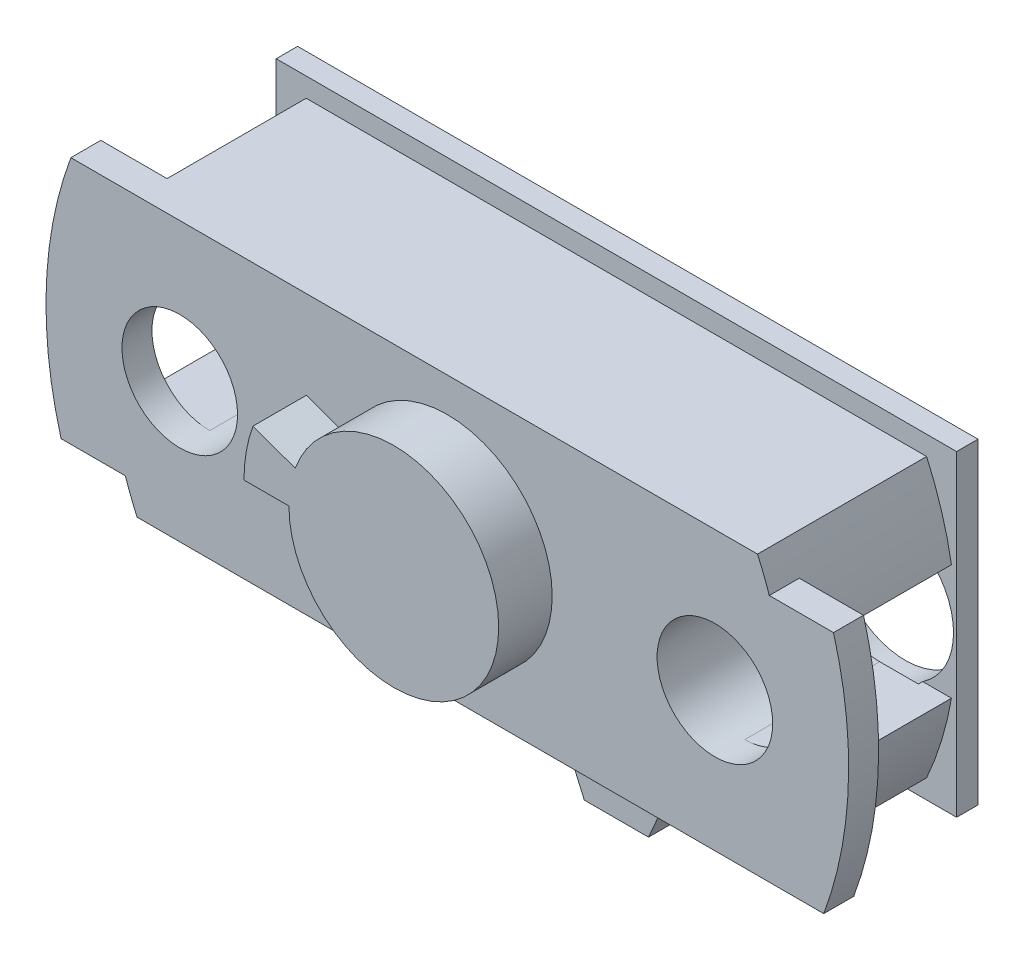
SolidWorks part; units mm, degrees
ref_plane "Přední rovina" through (0, 0, 0) normal (0, 0, 1) x (1, 0, 0)
ref_plane "Horní rovina" through (0, 0, 0) normal (0, 1, 0) x (1, 0, 0)
ref_plane "Pravá rovina" through (0, 0, 0) normal (1, 0, 0) x (0, 0, -1)
sketch "Skica1" plane through (0, 0, 0) normal (0, 0, 1) x (1, 0, 0)
  line L0 (-17.5873, 6.5) -> (17.5873, 6.5)
  line L1 (-17.5873, -6.5) -> (17.5873, -6.5)
  line L2 (-18.0431, 5.1) -> (-15.0431, 5.1)
  line L3 (-15.0431, 5.1) -> (-15.0431, 6.5)
  line L4 (18.0431, -5.1) -> (15.0431, -5.1)
  line L5 (15.0431, -5.1) -> (15.0431, -6.5)
  line L6 (-18.0431, -5.1) -> (-15.0431, -5.1)
  line L7 (-15.0431, -5.1) -> (-15.0431, -6.5)
  line L8 (18.0431, 5.1) -> (15.0431, 5.1)
  line L9 (15.0431, 5.1) -> (15.0431, 6.5)
  arc A0 (-17.5873, 6.5) -> (-17.5873, -6.5) centre (0, 0) ccw
  arc A1 (17.5873, -6.5) -> (17.5873, 6.5) centre (0, 0) ccw
  dimension "D1" = 37.5
  dimension "D2" = 13
  dimension "D3" = 1.4
  dimension "D4" = 1.4
  dimension "D5" = 3
  dimension "D6" = 3
extrude "Přidat vysunutím1" add sketch "Skica1" along normal blind 1.4 contours L4 A1 L0 L3 L2 A0 L1 L5 | L0 A0 L2 L3 | L1 A1 L4 L5
sketch "Skica2" plane through (0, 0, 1.4) normal (0, 0, 1) x (1, 0, 0)
  line L0 (0, 0) -> (-6.5778, 2.3941)
  line L1 (0, 0) -> (-7, 0)
  circle A0 centre (0, 0) radius 4.9
  circle A1 centre (0, 0) radius 7
  dimension "D1" = 9.8
  dimension "D2" = 14
  dimension "D3" = 20
extrude "Přidat vysunutím2" add sketch "Skica2" along normal blind 2.5 contours L1 A0 L0 | L0 A0 L1 | L0 A1 L1 A0
sketch "Skica3" plane through (0, 0, 1.4) normal (0, 0, 1) x (1, 0, 0)
  circle A0 centre (-12.5, 0) radius 2.7
  circle A1 centre (12.5, 0) radius 2.7
  dimension "D1" = 5.4
  dimension "D2" = 5.4
  dimension "D3" = 25
  dimension "D4" = 12.5
extrude "Odebrat vysunutím1" cut sketch "Skica3" against normal blind 2.5
sketch "Skica4" plane through (0, 0, 0) normal (0, 0, -1) x (-1, 0, 0)
  line L0 (-14.4932, 6.5) -> (14.4932, 6.5)
  line L1 (17.5873, 6.5) -> (-15.0431, 6.5) construction
  line L2 (-14.4932, -6.5) -> (14.4932, -6.5)
  line L3 (15.0431, -6.5) -> (-17.5873, -6.5) construction
  line L4 (-12.5, 2.7) -> (-15.6529, 2.7)
  line L5 (-12.5, -2.7) -> (-15.6529, -2.7)
  line L6 (12.5, 2.7) -> (15.6529, 2.7)
  line L7 (12.5, -2.7) -> (15.6529, -2.7)
  arc A0 (-14.4932, 6.5) -> (-14.4932, -6.5) centre (0, 0) ccw
  arc A1 (14.4932, -6.5) -> (14.4932, 6.5) centre (0, 0) ccw
  circle A2 centre (-12.5, 0) radius 2.7
  circle A3 centre (12.5, 0) radius 2.7
  circle A4 centre (-12.5, 0) radius 2.7 construction
  circle M6 centre (12.5, 0) radius 2.7
  circle M7 centre (-12.5, 0) radius 2.7
  line M8 (17.5873, 6.5) -> (-15.0431, 6.5)
  line M12 (-17.5873, -6.5) -> (15.0431, -6.5)
extrude "Přidat vysunutím3" add sketch "Skica4" along normal blind 7.5 contours L6 A1 A0 L4 L5 L7 M8 M7 M12 M6
sketch "Skica5" plane through (0, 0, 0) normal (0, 0, -1) x (-1, 0, 0)
  line L0 (-14.4932, 6.5) -> (-15.0431, 6.5)
  line L1 (-15.0431, 6.5) -> (-15.0431, 5.1)
  line L2 (14.4932, -6.5) -> (15.0431, -6.5)
  line L3 (15.0431, -6.5) -> (15.0431, -5.1)
  circle A0 centre (0, 0) radius 15.8841
extrude "Odebrat vysunutím2" cut sketch "Skica5" against normal blind 7.5 contours A0 L2 L3 | A0 L0 L1
sketch "Skica9" plane through (0, 0, -7.5) normal (0, 0, -1) x (-1, 0, 0)
  line L0 (14.4932, 6.5) -> (-14.4932, 6.5) construction
  line L1 (-15.8932, 7.4) -> (15.8932, 7.4)
  line L2 (-15.8932, 7.4) -> (-15.8932, -7.4)
  line L3 (-15.8932, -7.4) -> (15.8932, -7.4)
  line L4 (15.8932, 7.4) -> (15.8932, -7.4)
  line L5 (-14.4932, -6.5) -> (14.4932, -6.5) construction
  line L6 (0, 0) -> (0, 7.4) construction
  point P10 (0, 0)
  point P14 (-29.3555, 12.3514)
  dimension "D2" = 0.9
  dimension "D3" = 0.9
  dimension "D4" = 1.4
  dimension "D5" = 1.4
extrude "Přidat vysunutím5" add sketch "Skica9" against normal blind 1
sketch "Skica6" plane through (0, 0, -7.5) normal (0, 0, -1) x (-1, 0, 0)
  circle A0 centre (-12.5, 0) radius 3.25
  circle A1 centre (12.5, 0) radius 3.25
  dimension "D1" = 6.5
  dimension "D2" = 6.5
extrude "Odebrat vysunutím3" cut sketch "Skica6" against normal blind 1.2
sketch "Skica7" plane through (0, 0, -7.5) normal (0, 0, -1) x (-1, 0, 0)
  line L0 (-10.0833, -4.829) -> (10.0833, 4.829) construction
  line L2 (0, 0) -> (0, 7.4) construction
  line L3 (15.8932, 7.4) -> (-15.8932, 7.4) construction
  circle A0 centre (10.0833, 4.829) radius 0.95
  circle A1 centre (-10.0833, -4.829) radius 0.95
  circle A2 centre (-12.5, 0) radius 3.25 construction
  arc A3 (-14.309, -2.7) -> (-14.309, 2.7) centre (-12.5, 0) ccw construction
  point P19 (0, 0)
  dimension "D1" = 1.9
  dimension "D2" = 1.9
  dimension "D3" = 22.36
  dimension "D4" = 5.4
extrude "Odebrat vysunutím5" cut sketch "Skica7" against normal blind 7
sketch "Skica12" plane through (0, 0, -7.5) normal (0, 0, -1) x (-1, 0, 0)
  line L0 (-5, -7.4) -> (-1.5, -15.4)
  line L1 (-15.8932, -7.4) -> (15.8932, -7.4) construction
  line L2 (-1.5, -15.4) -> (1.5, -15.4)
  line L3 (1.5, -15.4) -> (5, -7.4)
  line L5 (-5, -7.4) -> (5, -7.4)
  point P4 (0, -15.4)
  point P7 (0, -7.4)
  dimension "D1" = 8
  dimension "D2" = 3
  dimension "D3" = 10
  dimension "D4" = 5
extrude "Přidat vysunutím7" add sketch "Skica12" against normal blind 1 contours L3 L5 L0 L2
